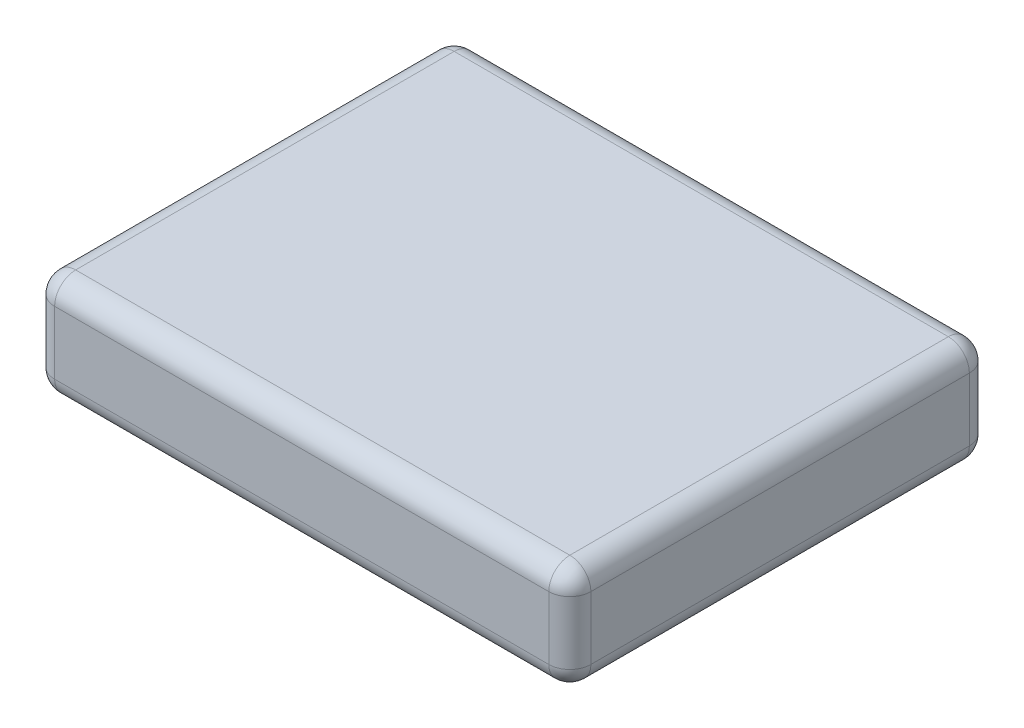
SolidWorks part; units mm, degrees
ref_plane "Front Plane" through (0, 0, 0) normal (0, 0, 1) x (1, 0, 0)
ref_plane "Top Plane" through (0, 0, 0) normal (0, 1, 0) x (1, 0, 0)
ref_plane "Right Plane" through (0, 0, 0) normal (1, 0, 0) x (0, 0, -1)
sketch "Sketch1" plane through (0, 0, 0) normal (0, 1, 0) x (1, 0, 0)
  line L1 (-12.75, -10) -> (12.75, -10)
  line L2 (-12.75, -10) -> (-12.75, 10)
  line L3 (-12.75, 10) -> (12.75, 10)
  line L4 (12.75, -10) -> (12.75, 10)
  line L5 (-12.75, -10) -> (12.75, 10) construction
  line L6 (-12.75, 10) -> (12.75, -10) construction
  point P0 (0, 0)
  dimension "D1" = 25.5
  dimension "D2" = 20
extrude "Boss-Extrude1" add sketch "Sketch1" along normal blind 5
fillet "Fillet1" radius 1 12 edges at (-12.75, 2.5, -10) (-12.75, 2.5, 10) (12.75, 2.5, 10) (12.75, 2.5, -10) (0, 0, -10) (-12.75, 0, 0) (0, 0, 10) (12.75, 0, 0) (0, 5, 10) (-12.75, 5, 0) (0, 5, -10) (12.75, 5, 0)
